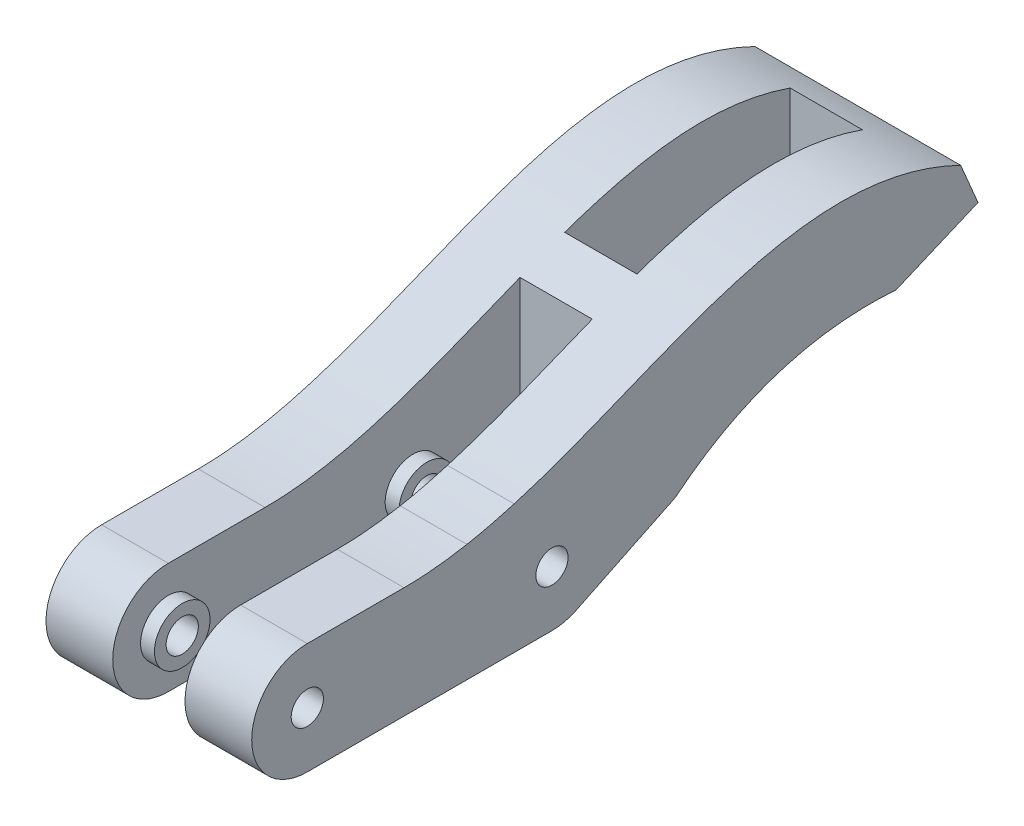
SolidWorks part; units mm, degrees
ref_plane "Front Plane" through (0, 0, 0) normal (0, 0, 1) x (1, 0, 0)
ref_plane "Top Plane" through (0, 0, 0) normal (0, 1, 0) x (1, 0, 0)
ref_plane "Right Plane" through (0, 0, 0) normal (1, 0, 0) x (0, 0, -1)
sketch "Sketch1" plane through (0, 0, 0) normal (1, 0, 0) x (0, 0, -1)
  line L1 (0, 0) -> (27, 0)
  line L2 (0, 0) -> (0, 10)
  line L3 (0, 10) -> (27, 10)
  circle A0 centre (5, 5) radius 1.45
  circle A1 centre (5, 5) radius 5
  circle A2 centre (27, 5) radius 5
  circle A3 centre (27, 5) radius 1.45
  dimension "D7" = 2.9
  dimension "D11" = 10
  dimension "D2" = 2.9
  dimension "D1" = 10
  dimension "D8" = 5
  dimension "D9" = 5
  dimension "D10" = 22
extrude "Boss-Extrude1" add sketch "Sketch1" along normal blind 8.5 contours A1 A0 | A2 L3 A1 L1 | A2 A3 | L2 A1 | L1 A1
sketch "Sketch2" plane through (8.5, 0, 0) normal (1, 0, 0) x (0, 0, -1)
  line L6 (5, 10) -> (27, 10) construction
  line L14 (5, 10) -> (27, 10)
  line L20 (29.1838, 0.5021) -> (38.0854, 4.8241)
  line L21 (57.948, 11.0678) -> (65.3138, 14.1895)
  line L22 (65.3138, 14.1895) -> (63.753, 17.8724)
  arc A3 (27, 0) -> (27, 10) centre (27, 5) ccw construction
  arc A4 (27, 0) -> (27, 10) centre (27, 5) ccw
  spline S0 degree 2 poles (38.0854, 4.8241) (46.7975, 11.8952) (57.948, 11.0678) knots 0 0 0 1 1 1
  spline S1 degree 3 poles (63.753, 17.8724) (45.9289, 26.5638) (31.0593, 10) (13.695, 10) knots 0 0 0 0 1 1 1 1
  point P2 (27, 5)
  dimension "D3" = 4
  dimension "D4" = 8
extrude "Boss-Extrude2" add sketch "Sketch2" against normal blind 8.5
sketch "Sketch3" plane through (8.5, 0, 0) normal (1, 0, 0) x (0, 0, -1)
  line L0 (36.1081, 3.864) -> (33.1217, 15.0474)
  line L1 (29.1838, 0.5021) -> (38.0854, 4.8241) construction
  line L7 (13.695, 10) -> (5, 10)
  line L8 (5, 0) -> (27, 0)
  line L9 (29.1838, 0.5021) -> (38.0854, 4.8241)
  line L10 (57.948, 11.0678) -> (65.3138, 14.1895)
  line L11 (65.3138, 14.1895) -> (63.753, 17.8724)
  line L14 (36.1081, 3.864) -> (38.0854, 4.8241)
  line L15 (57.948, 11.0678) -> (65.3138, 14.1895)
  line L16 (65.3138, 14.1895) -> (63.753, 17.8724)
  arc A2 (5, 10) -> (5, 0) centre (5, 5) ccw
  arc A3 (27, 0) -> (29.1838, 0.5021) centre (27, 5) ccw
  parabola Q1 (38.0854, 4.8241) -> (57.948, 11.0678) focus (51.4029, -2.5663) apex (47.5356, 9.9606)
  parabola Q2 (38.0854, 4.8241) -> (57.948, 11.0678) focus (51.4029, -2.5663) apex (47.5356, 9.9606)
  spline S0 degree 3 poles (63.753, 17.8724) (45.9289, 26.5638) (31.0593, 10) (13.695, 10) knots 0 0 0 0 1 1 1 1 construction
  spline S2 degree 3 poles (759.8744, -3918.1569) (-408.6489, 4064.3723) (489.4103, -4029.4208) (-733.2275, 3935.2795) knots -3.97833 -3.97833 -3.97833 -3.97833 5.181082 5.181082 5.181082 5.181082 only from (63.753, 17.8724) to (13.695, 10)
  spline S3 degree 3 poles (63.753, 17.8724) (52.8531, 23.1874) (43.0581, 19.0579) (33.1217, 15.0474) knots 0 0 0 0 0.611526 0.611526 0.611526 0.611526
  dimension "D1" = 0
extrude "Boss-Extrude3" add sketch "Sketch3" along normal blind 10
sketch "Sketch4" plane through (8.5, 0, 0) normal (1, 0, 0) x (0, 0, -1)
  circle A3 centre (5, 5) radius 5
extrude "Boss-Extrude4" add sketch "Sketch4" along normal blind 10
sketch "Sketch5" plane through (8.5, 0, 0) normal (1, 0, 0) x (0, 0, -1)
  line L0 (5, 10) -> (13.695, 10)
  line L1 (13.695, 10) -> (13.695, 0)
  line L2 (5, 0) -> (27, 0) construction
  line L3 (13.695, 0) -> (5, 0)
  line L8 (13.695, 10) -> (5, 10)
  line L9 (5, 0) -> (27, 0)
  line L10 (29.1838, 0.5021) -> (36.1081, 3.864)
  line L11 (36.1081, 3.864) -> (33.1217, 15.0474)
  arc A2 (5, 0) -> (5, 10) centre (5, 5) ccw
  arc A3 (27, 0) -> (29.1838, 0.5021) centre (27, 5) ccw
  arc A4 (5, 0) -> (5, 10) centre (5, 5) ccw
  spline S1 degree 3 poles (299.4274, -948.8411) (-49.3626, 1053.943) (122.0139, -1022.0164) (-248.6358, 974.9634) knots -2.297236 -2.297236 -2.297236 -2.297236 3.50094 3.50094 3.50094 3.50094 only from (33.1217, 15.0474) to (13.695, 10)
  dimension "D1" = 0
extrude "Boss-Extrude5" add sketch "Sketch5" along normal blind 10
sketch "Sketch6" plane through (8.5, 0, 0) normal (1, 0, 0) x (0, 0, -1)
  line L0 (19.3553, 10.5481) -> (21.3201, 0)
  line L1 (13.695, 0) -> (27, 0) construction
  line L6 (13.695, 10) -> (13.695, 0)
  line L7 (13.695, 0) -> (27, 0)
  line L8 (29.1838, 0.5021) -> (36.1081, 3.864)
  line L9 (36.1081, 3.864) -> (33.1217, 15.0474)
  line L10 (13.695, 10) -> (13.695, 0)
  line L11 (13.695, 0) -> (21.3201, 0)
  arc A1 (27, 0) -> (29.1838, 0.5021) centre (27, 5) ccw
  spline S0 degree 3 poles (33.1217, 15.0474) (26.8097, 12.4997) (20.4406, 10) (13.695, 10) knots 0.611526 0.611526 0.611526 0.611526 1 1 1 1 construction
  spline S2 degree 3 poles (759.155, -3913.2428) (-408.2834, 4061.0712) (489.1642, -4027.8291) (-733.2374, 3935.3436) knots -3.97645 -3.97645 -3.97645 -3.97645 5.181106 5.181106 5.181106 5.181106 only from (33.1217, 15.0474) to (13.695, 10)
  spline S3 degree 3 poles (19.3553, 10.5481) (17.494, 10.2014) (15.6096, 10) (13.695, 10) knots 0.889736 0.889736 0.889736 0.889736 1 1 1 1
  dimension "D1" = 0
extrude "Boss-Extrude6" add sketch "Sketch6" along normal blind 10
sketch "Sketch7" plane through (8.5, 0, 0) normal (1, 0, 0) x (0, 0, -1)
  line L0 (32.646, 2.1831) -> (28.5094, 13.2352)
  line L1 (29.1838, 0.5021) -> (36.1081, 3.864) construction
  line L6 (19.3553, 10.5481) -> (21.3201, 0)
  line L7 (21.3201, 0) -> (27, 0)
  line L8 (29.1838, 0.5021) -> (36.1081, 3.864)
  line L9 (36.1081, 3.864) -> (33.1217, 15.0474)
  line L12 (32.646, 2.1831) -> (36.1081, 3.864)
  line L13 (36.1081, 3.864) -> (33.1217, 15.0474)
  arc A1 (27, 0) -> (29.1838, 0.5021) centre (27, 5) ccw
  spline S0 degree 3 poles (33.1217, 15.0474) (28.6013, 13.2228) (24.0516, 11.4229) (19.3553, 10.5481) knots 0.611526 0.611526 0.611526 0.611526 0.889736 0.889736 0.889736 0.889736 construction
  spline S2 degree 3 poles (759.1402, -3913.1411) (-408.2259, 4060.662) (489.0823, -4027.1047) (-733.0808, 3934.3239) knots -3.976411 -3.976411 -3.976411 -3.976411 5.180715 5.180715 5.180715 5.180715 only from (33.1217, 15.0474) to (19.3553, 10.5481)
  spline S3 degree 3 poles (33.1217, 15.0474) (31.5892, 14.4288) (30.0533, 13.8131) (28.5094, 13.2352) knots 0.611526 0.611526 0.611526 0.611526 0.705846 0.705846 0.705846 0.705846
  dimension "D1" = 0
extrude "Boss-Extrude7" add sketch "Sketch7" along normal blind 10
sketch "Sketch8" plane through (8.5, 0, 0) normal (1, 0, 0) x (0, 0, -1)
  line L0 (27, 0) -> (23.6043, 11.5781)
  line L5 (29.1838, 0.5021) -> (32.646, 2.1831)
  line L6 (32.646, 2.1831) -> (28.5094, 13.2352)
  line L7 (19.3553, 10.5481) -> (21.3201, 0)
  line L8 (21.3201, 0) -> (27, 0)
  line L9 (29.1838, 0.5021) -> (32.646, 2.1831)
  line L10 (32.646, 2.1831) -> (28.5094, 13.2352)
  arc A1 (27, 0) -> (29.1838, 0.5021) centre (27, 5) ccw
  arc A2 (27, 0) -> (29.1838, 0.5021) centre (27, 5) ccw
  spline S0 degree 3 poles (28.5094, 13.2352) (25.4995, 12.1087) (22.4594, 11.1263) (19.3553, 10.5481) knots 0.705846 0.705846 0.705846 0.705846 0.889736 0.889736 0.889736 0.889736 construction
  spline S2 degree 3 poles (759.2078, -3913.6033) (-408.2617, 4060.9821) (489.1077, -4027.2739) (-733.0843, 3934.3467) knots -3.976588 -3.976588 -3.976588 -3.976588 5.180724 5.180724 5.180724 5.180724 only from (28.5094, 13.2352) to (19.3553, 10.5481)
  spline S3 degree 3 poles (28.5094, 13.2352) (26.885, 12.6272) (25.2517, 12.0612) (23.6043, 11.5781) knots 0.705846 0.705846 0.705846 0.705846 0.805092 0.805092 0.805092 0.805092
  dimension "D1" = 0
extrude "Boss-Extrude8" add sketch "Sketch8" along normal blind 10
sketch "Sketch9" plane through (8.5, 0, 0) normal (1, 0, 0) x (0, 0, -1)
  line L0 (23.6043, 11.5781) -> (27, 0)
  line L1 (27, 0) -> (21.3201, 0)
  line L2 (21.3201, 0) -> (19.3553, 10.5481)
  spline S0 degree 3 poles (19.3553, 10.5481) (20.7889, 10.8151) (22.2054, 11.1678) (23.6043, 11.5781) knots 0 0 0 0 1 1 1 1
  spline S1 degree 3 poles (23.6043, 11.5781) (22.1993, 11.166) (20.7841, 10.8142) (19.3553, 10.5481) knots 0.805092 0.805092 0.805092 0.805092 0.889736 0.889736 0.889736 0.889736 construction
extrude "Boss-Extrude9" add sketch "Sketch9" along normal blind 10
sketch "Sketch10" plane through (0, 0, 0) normal (-1, 0, 0) x (0, 0, 1)
  circle A0 centre (-27, 5) radius 1.45
  circle A1 centre (-5, 5) radius 1.45
extrude "Cut-Extrude2" cut sketch "Sketch10" against normal blind 28 contours A0 | A1
sketch "Sketch11" plane through (0, 10, 0) normal (0, 1, 0) x (1, 0, 0)
  line L0 (0, 5) -> (6, 5)
  line L1 (18.5, 5) -> (0, 5) construction
  line L2 (18.5, 5) -> (12.5, 5)
  line L3 (0, 0) -> (18.5, 0) construction
  line L4 (6, 5) -> (12.5, 5)
  line L5 (6, 5) -> (6, 0)
  line L6 (6, 0) -> (12.5, 0)
  line L7 (12.5, 5) -> (12.5, 0)
  line L9 (6, 5) -> (12.5, 5)
  line L10 (6, 5) -> (6, 36.6274)
  line L11 (6, 36.6274) -> (12.5, 36.6274)
  line L12 (12.5, 5) -> (12.5, 36.6274)
  line M1 (18.5, 13.695) -> (0, 13.695)
  line M3 (0, 5) -> (18.5, 5)
extrude "Cut-Extrude3" cut sketch "Sketch11" against normal blind 49 contours L12 L11 L10 M1 | L7 L5 L6 M3 | L12 L10 M3 M1
sketch "Sketch12" plane through (0, 10, 0) normal (0, -1, 0) x (-1, 0, 0)
  line L1 (-6, 36.6274) -> (-12.5, 36.6274)
  line L2 (-6, 36.6274) -> (-6, 13.695)
  line L3 (-6, 13.695) -> (-12.5, 13.695)
  line L4 (-12.5, 36.6274) -> (-12.5, 13.695)
extrude "Cut-Extrude4" cut sketch "Sketch12" against normal blind 49
sketch "Sketch14" plane through (0, 0, 0) normal (0, -1, 0) x (1, 0, 0)
  line L1 (6, -36.6274) -> (12.5, -36.6274)
  line L2 (6, -36.6274) -> (6, -60.9173)
  line L3 (6, -60.9173) -> (12.5, -60.9173)
  line L4 (12.5, -36.6274) -> (12.5, -60.9173)
  line L5 (6, -40.6435) -> (12.5, -40.6435)
  line L6 (6, -40.6435) -> (6, -60.9173)
  line L7 (6, -60.9173) -> (12.5, -60.9173)
  line L8 (12.5, -40.6435) -> (12.5, -60.9173)
extrude "Cut-Extrude5" cut sketch "Sketch14" against normal blind 49 contours L5 L2 L3 L4
sketch "Sketch17" plane through (12.5, 0, 0) normal (-1, 0, 0) x (0, 0, 1)
  circle A0 centre (-5, 5) radius 2.5
  circle A1 centre (-5, 5) radius 1.45
extrude "Boss-Extrude10" add sketch "Sketch17" along normal blind 1.25
sketch "Sketch18" plane through (6, 0, 0) normal (1, 0, 0) x (0, 0, -1)
  circle A0 centre (5, 5) radius 2.5
  circle A1 centre (5, 5) radius 1.45
extrude "Boss-Extrude11" add sketch "Sketch18" along normal blind 1.25
sketch "Sketch19" plane through (6, 0, 0) normal (1, 0, 0) x (0, 0, -1)
  circle A0 centre (27, 5) radius 2.5
  circle A1 centre (27, 5) radius 1.45
extrude "Boss-Extrude12" add sketch "Sketch19" along normal blind 1.25 contours A0
sketch "Sketch21" plane through (12.5, 0, 0) normal (-1, 0, 0) x (0, 0, 1)
  circle A0 centre (-27, 5) radius 2.5
  circle A1 centre (-27, 5) radius 1.45
extrude "Boss-Extrude13" add sketch "Sketch21" along normal blind 1.25
sketch "Sketch22" plane through (12.5, 0, 0) normal (-1, 0, 0) x (0, 0, 1)
  circle A0 centre (-27, 5) radius 1.45
extrude "Cut-Extrude6" cut sketch "Sketch22" along normal through all
